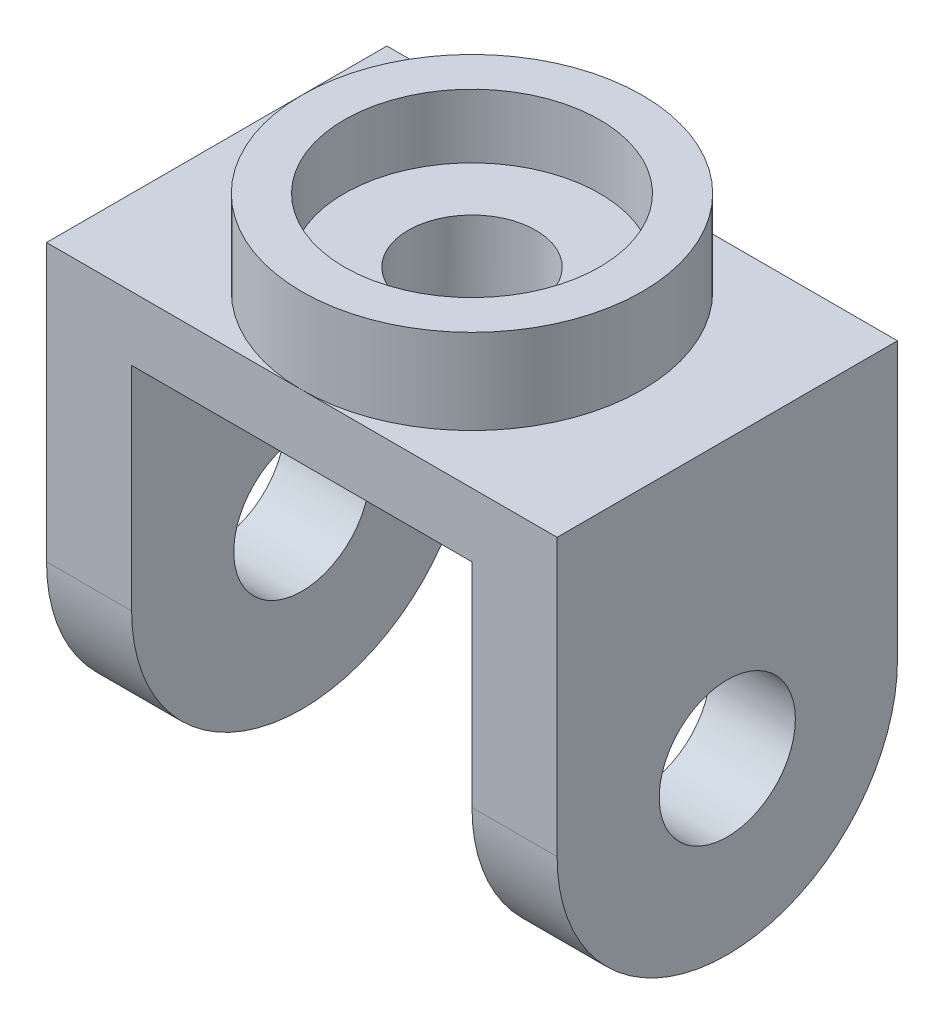
SolidWorks part; units mm, degrees
ref_plane "Front Plane" through (0, 0, 0) normal (0, 0, 1) x (1, 0, 0)
ref_plane "Top Plane" through (0, 0, 0) normal (0, 1, 0) x (1, 0, 0)
ref_plane "Right Plane" through (0, 0, 0) normal (1, 0, 0) x (0, 0, -1)
sketch "Sketch1" plane through (0, 0, 0) normal (0, 1, 0) x (1, 0, 0)
  line L1 (-60, 40) -> (60, 40)
  line L2 (-60, 40) -> (-60, -40)
  line L3 (-60, -40) -> (60, -40)
  line L4 (60, 40) -> (60, -40)
  line L5 (-60, 40) -> (60, -40) construction
  line L6 (-60, -40) -> (60, 40) construction
  point P0 (0, 0)
  dimension "D1" = 80
  dimension "D2" = 120
extrude "Boss-Extrude1" add sketch "Sketch1" along normal blind 15 contours L2 L3 L4 L1
sketch "Sketch2" plane through (0, 15, 0) normal (0, 1, 0) x (1, 0, 0)
  circle A0 centre (0, 0) radius 40
  dimension "D1" = 80
extrude "Boss-Extrude2" add sketch "Sketch2" along normal blind 20 contours A0
sketch "Sketch3" plane through (0, 35, 0) normal (0, 1, 0) x (1, 0, 0)
  circle A0 centre (0, 0) radius 30
  dimension "D1" = 60
extrude "Cut-Extrude3" cut sketch "Sketch3" against normal blind 15
sketch "Sketch4" plane through (0, 20, 0) normal (0, 1, 0) x (1, 0, 0)
  circle A0 centre (0, 0) radius 15
  dimension "D1" = 30
extrude "Cut-Extrude4" cut sketch "Sketch4" against normal blind 29
sketch "Sketch5" plane through (60, 0, 0) normal (1, 0, 0) x (0, 0, -1)
  line L0 (0, -13.7009) -> (0, -97.725) construction
  line L1 (-40, 0) -> (40, 0)
  line L2 (-40, 0) -> (-40, -50)
  line L4 (40, 0) -> (40, -50)
  arc A0 (-40, -50) -> (40, -50) centre (0, -50) ccw
  dimension "D3" = 40
  dimension "D1" = 80
  dimension "D2" = 50
extrude "Boss-Extrude5" add sketch "Sketch5" against normal blind 20 contours L2 A0 L4 L1
sketch "Sketch8" plane through (60, 0, 0) normal (1, 0, 0) x (0, 0, -1)
  circle A0 centre (0, -50) radius 16
  dimension "D1" = 32
extrude "Cut-Extrude6" cut sketch "Sketch8" against normal blind 20
mirror "Mirror1" about plane through (0, 0, 0) normal (1, 0, 0) of "Boss-Extrude5", "Cut-Extrude6"
